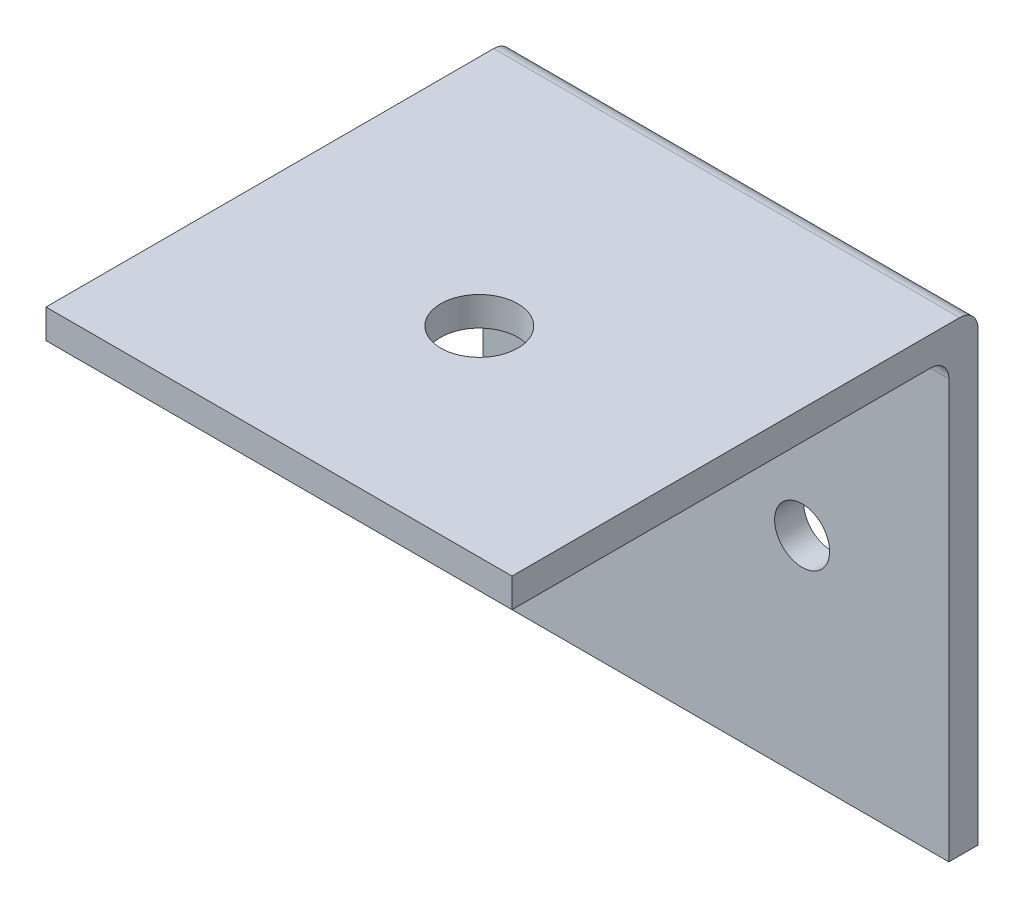
SolidWorks part; units mm, degrees
material "6061-T4 (SS)"
ref_plane "Front Plane" through (0, 0, 0) normal (0, 0, 1) x (1, 0, 0)
ref_plane "Top Plane" through (0, 0, 0) normal (0, 1, 0) x (1, 0, 0)
ref_plane "Right Plane" through (0, 0, 0) normal (1, 0, 0) x (0, 0, -1)
sketch "Sketch1" plane through (0, 0, 0) normal (1, 0, 0) x (0, 0, -1)
  line L1 (11.1125, -12.7) -> (12.7, -12.7)
  line L2 (-12.7, 11.1125) -> (-12.7, 12.7)
  line L3 (-12.7, 12.7) -> (11.7, 12.7)
  line L4 (12.7, -12.7) -> (12.7, 11.7)
  line L5 (0, 0) -> (12.7, 12.7) construction
  line L6 (-12.7, 12.7) -> (12.7, -12.7) construction
  line L9 (-12.7, 11.1125) -> (10.1125, 11.1125)
  line L10 (11.1125, -12.7) -> (11.1125, 10.1125)
  arc A0 (10.1125, 11.1125) -> (11.1125, 10.1125) centre (10.1125, 10.1125) cw
  arc A1 (11.7, 12.7) -> (12.7, 11.7) centre (11.7, 11.7) cw
  point P0 (0, 0)
  point P11 (11.1125, 11.1125)
  dimension "D4" = 1
  dimension "D5" = 1
  dimension "D1" = 25.4
  dimension "D2" = 25.4
  dimension "D3" = 1.5875
extrude "Boss-Extrude1" add sketch "Sketch1" along normal blind 25.4
sketch "Sketch2" plane through (0, 0, -11.1125) normal (0, 0, 1) x (1, 0, 0)
  line L0 (0, 10.1125) -> (0, -12.7) construction
  line L1 (25.4, 10.1125) -> (25.4, -12.7) construction
  circle A0 centre (8, -1.2937) radius 1.5
  circle A1 centre (17.4, -1.2937) radius 1.5
  dimension "D1" = 3
  dimension "D2" = 3
  dimension "D3" = 8
  dimension "D4" = 8
extrude "Cut-Extrude1" cut sketch "Sketch2" against normal blind 25.4
sketch "Sketch3" plane through (0, 11.1125, 0) normal (0, -1, 0) x (1, 0, 0)
  circle A0 centre (12.7, 1.7832) radius 2.1
  dimension "D1" = 4.2
extrude "Cut-Extrude2" cut sketch "Sketch3" against normal blind 25.4
